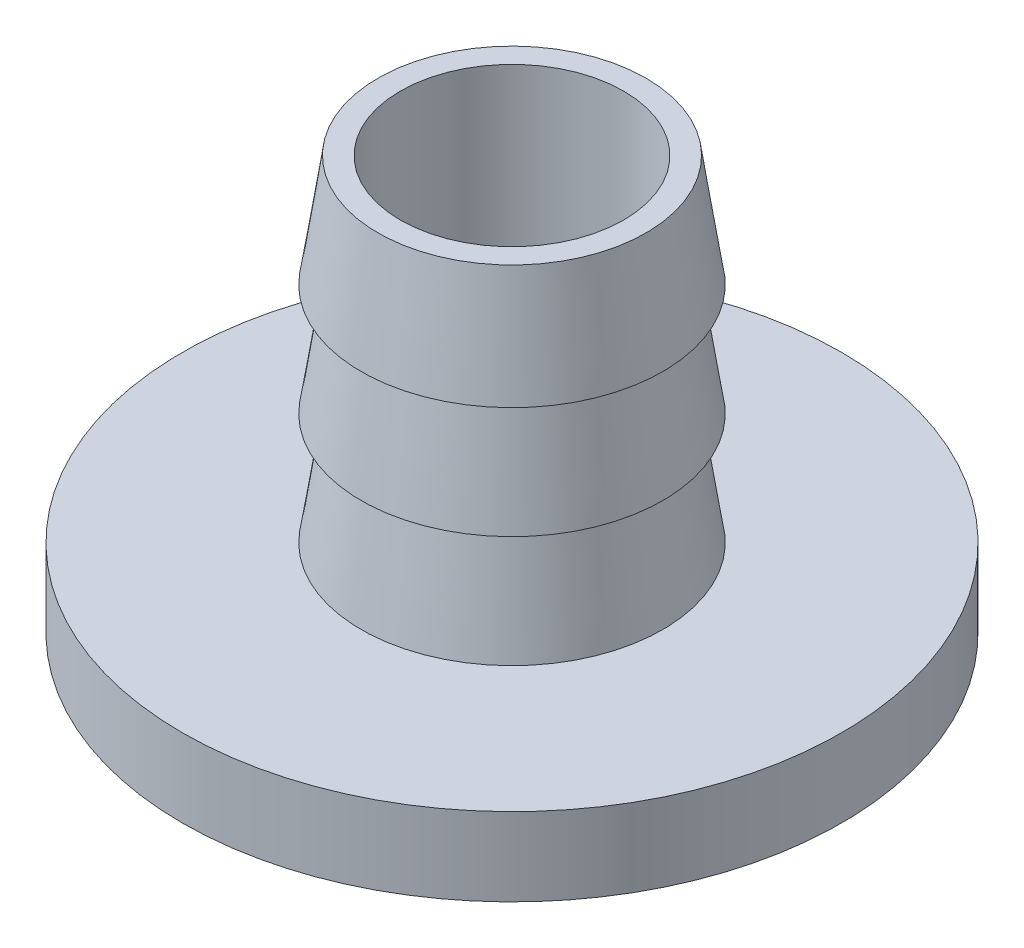
SolidWorks part; units mm, degrees
ref_plane "Front Plane" through (0, 0, 0) normal (0, 0, 1) x (1, 0, 0)
ref_plane "Top Plane" through (0, 0, 0) normal (0, 1, 0) x (1, 0, 0)
ref_plane "Right Plane" through (0, 0, 0) normal (1, 0, 0) x (0, 0, -1)
sketch "Sketch2" plane through (0, 0, 0) normal (0, 0, 1) x (1, 0, 0)
  line L0 (0, 0) -> (0, 32) construction
  line L1 (0, 32) -> (10, 32) construction
  line L2 (10, 32) -> (10, 0)
  line L3 (10, 0) -> (0, 0) construction
  line L4 (10, 0) -> (28.5, 0)
  line L5 (28.5, 0) -> (28.5, -5)
  line L6 (28.5, -5) -> (29.5, -5)
  line L7 (29.5, -5) -> (29.5, 2)
  line L8 (29.5, 2) -> (13.5, 2)
  line L9 (13.5, 2) -> (12, 12)
  line L10 (12, 12) -> (13.5, 12)
  line L11 (13.5, 12) -> (12, 22)
  line L12 (12, 22) -> (13.5, 22)
  line L13 (13.5, 22) -> (12, 32)
  line L14 (12, 32) -> (10, 32)
  point P3 (0, 0)
  point P16 (0, 0)
  dimension "D1" = 28.5
  dimension "D2" = 1
  dimension "D3" = 2
  dimension "D4" = 10
  dimension "D5" = 10
  dimension "D6" = 10
  dimension "D7" = 3.5
  dimension "D8" = 10
  dimension "D9" = 2
  dimension "D10" = 5
revolve "Revolve1" add sketch "Sketch2" angle 360 about L0
